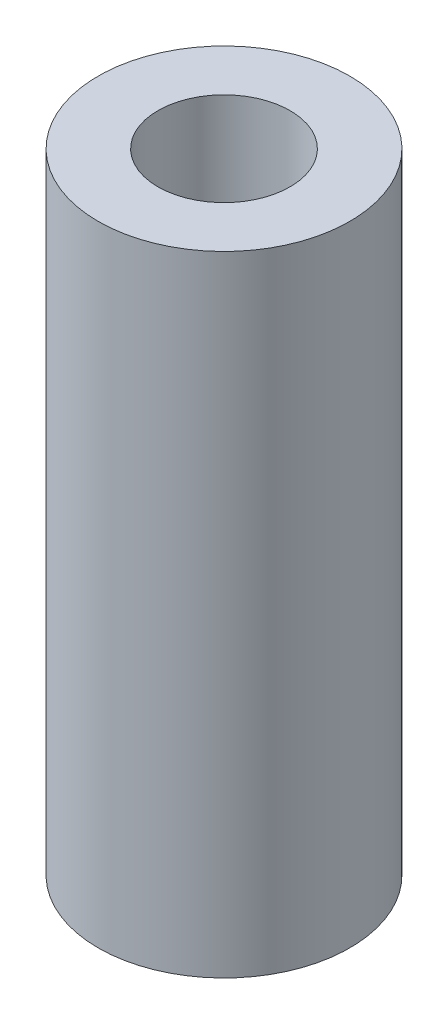
SolidWorks part; units mm, degrees
ref_plane "Front Plane" through (0, 0, 0) normal (0, 0, 1) x (1, 0, 0)
ref_plane "Top Plane" through (0, 0, 0) normal (0, 1, 0) x (1, 0, 0)
ref_plane "Right Plane" through (0, 0, 0) normal (1, 0, 0) x (0, 0, -1)
sketch "Sketch1" plane through (0, 0, 0) normal (0, 1, 0) x (1, 0, 0)
  circle A0 centre (0, 0) radius 4
  circle A1 centre (0, 0) radius 2.1
  dimension "D1" = 8
  dimension "D2" = 4.2
extrude "Boss-Extrude1" add sketch "Sketch1" along normal blind 20
